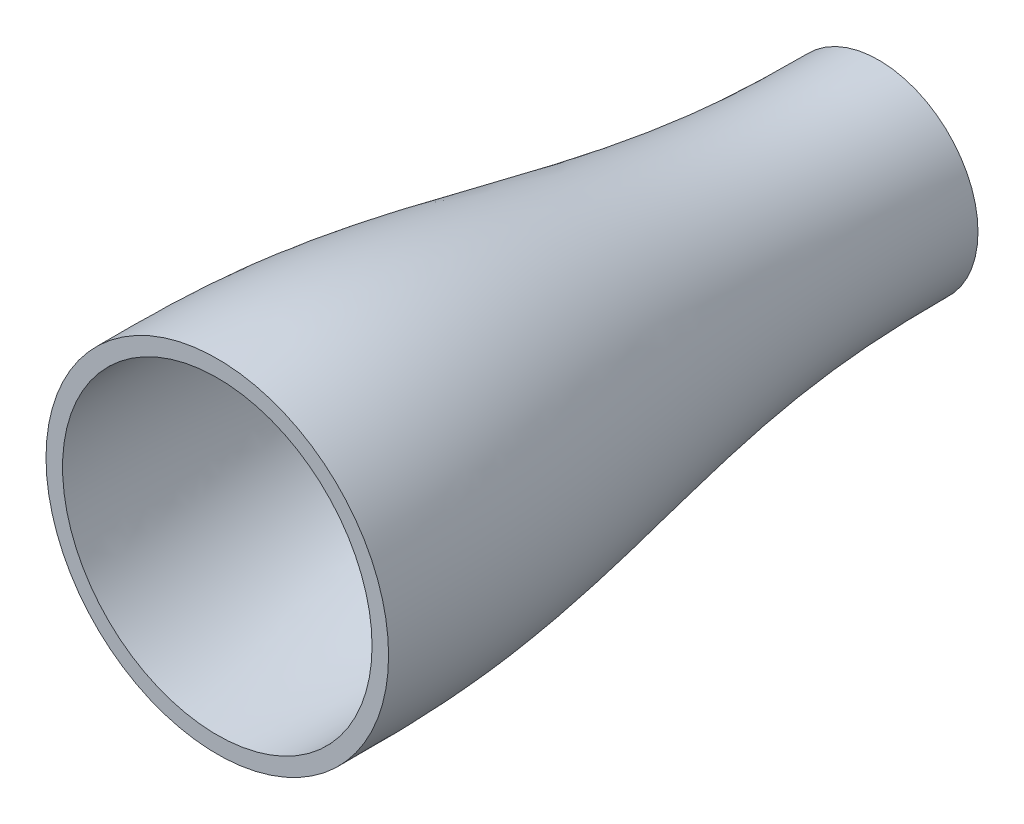
SolidWorks part; units mm, degrees
ref_plane "Alzado" through (0, 0, 0) normal (0, 0, 1) x (1, 0, 0)
ref_plane "Planta" through (0, 0, 0) normal (0, 1, 0) x (1, 0, 0)
ref_plane "Vista lateral" through (0, 0, 0) normal (1, 0, 0) x (0, 0, -1)
sketch "Croquis1" plane through (0, 0, 0) normal (1, 0, 0) x (0, 0, -1)
  line L0 (0, 0) -> (1200, 0) construction
  line L1 (0, 310.74) -> (0, 0)
  line L2 (0, 0) -> (1200, 0)
  line L3 (1200, 0) -> (1200, 180)
  spline S0 degree 5 poles (39.883, 300.3173) (279.8734, 302.4642) (519.8638, 304.6112) (761.0238, 176.0234) (1001.0142, 178.1703) (1241.0046, 180.3173) knots 0 0 0 0 0 0 1 1 1 1 1 1 construction
  spline S1 degree 5 poles (0, 310.74) (239.8981, 311.6434) (479.7963, 312.5468) (720.1535, 191.5444) (960.0987, 179.9507) (1200, 180) knots 0 0 0 0 0 0 0.965829 0.965829 0.965829 0.965829 0.965829 0.965829
  dimension "D1" = 310.74
  dimension "D2" = 180
revolve "Revolución2" add sketch "Croquis1" angle 360 about L2
ref_plane "Plano5" through (0, 0, 0) normal (0, 0, 1) x (1, 0, 0)
shell "Vaciado1" thickness 30
ref_plane "Plano3" through (0, 0, -1200) normal (0, 0, -1) x (-1, 0, 0)
